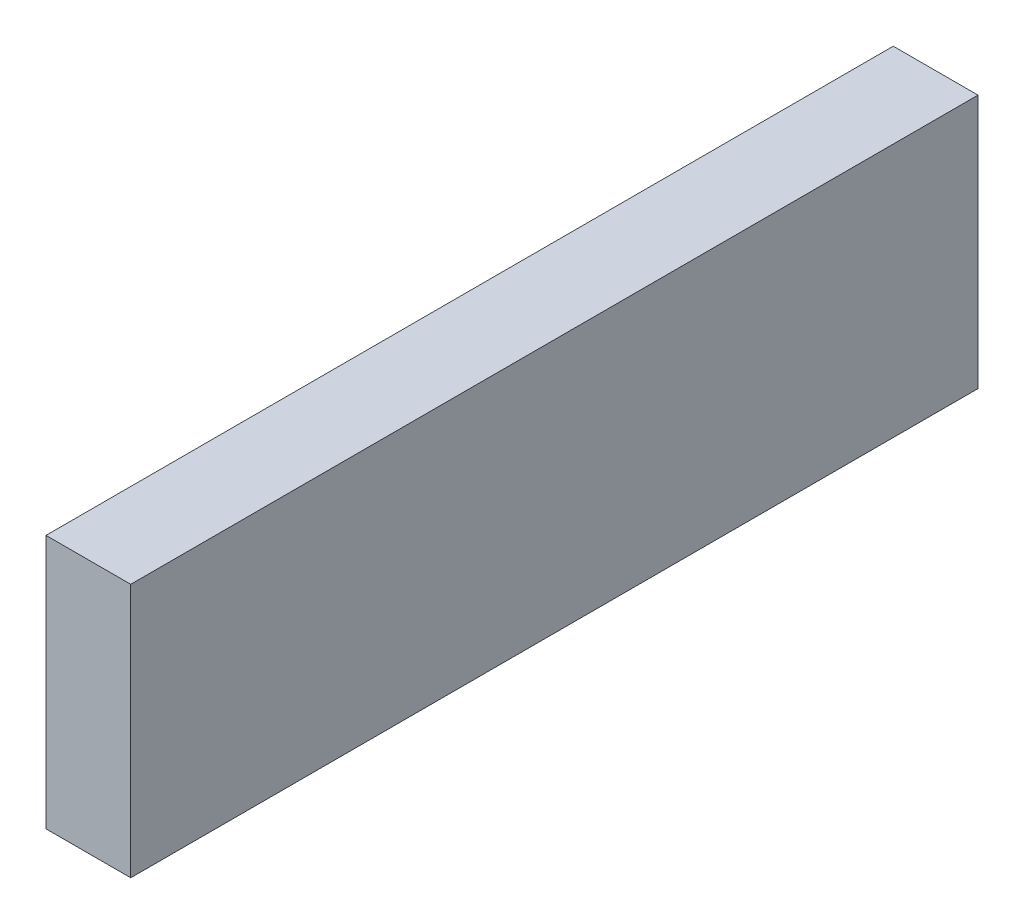
SolidWorks part; units mm, degrees
ref_plane "Front Plane" through (0, 0, 0) normal (0, 0, 1) x (1, 0, 0)
ref_plane "Top Plane" through (0, 0, 0) normal (0, 1, 0) x (1, 0, 0)
ref_plane "Right Plane" through (0, 0, 0) normal (1, 0, 0) x (0, 0, -1)
sketch "Sketch1" plane through (0, 0, 0) normal (0, 0, 1) x (1, 0, 0)
  line L1 (0, 0) -> (-50.8, 0)
  line L2 (0, 0) -> (0, 152.4)
  line L3 (0, 152.4) -> (-50.8, 152.4)
  line L4 (-50.8, 0) -> (-50.8, 152.4)
  dimension "D1" = 50.8
  dimension "D2" = 152.4
extrude "Boss-Extrude1" add sketch "Sketch1" along normal blind 508
